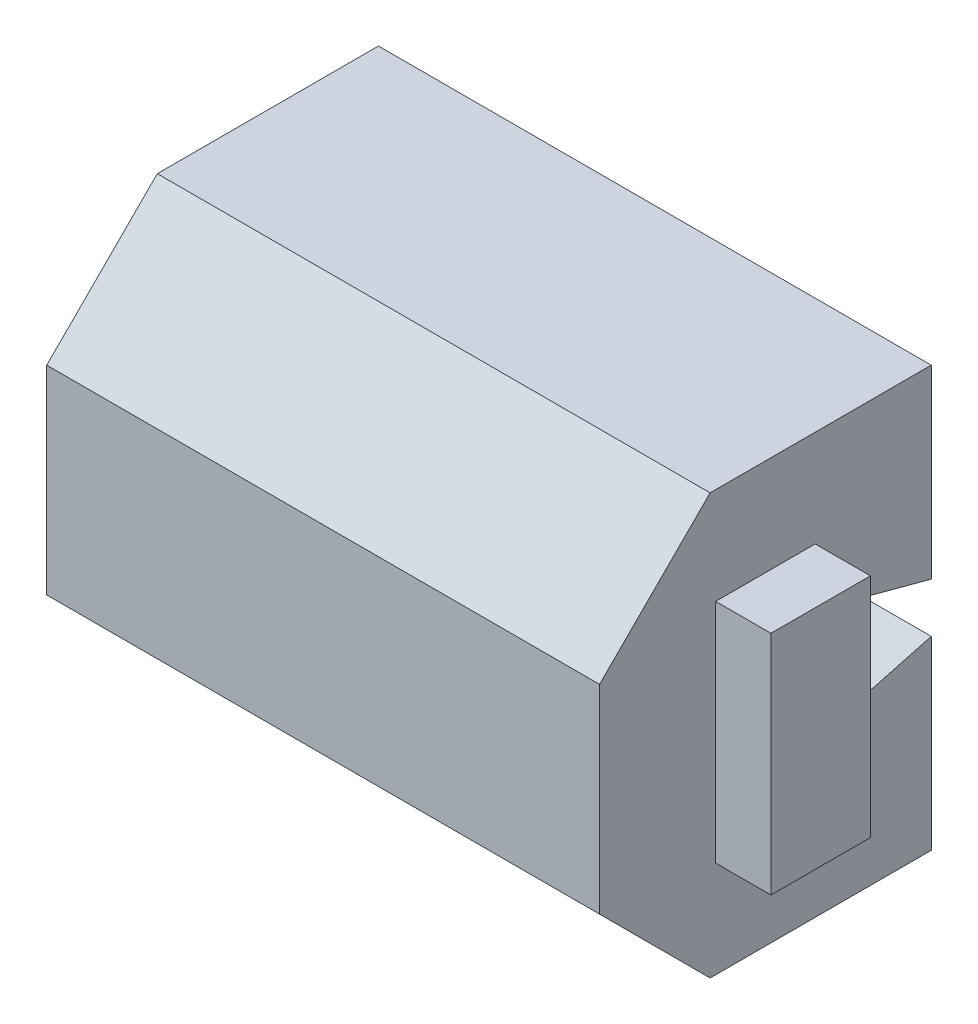
SolidWorks part; units mm, degrees
ref_plane "Piano frontale" through (0, 0, 0) normal (1, 0, 0) x (0, 1, 0)
ref_plane "Piano superiore" through (0, 0, 0) normal (0, 0, 1) x (0, 1, 0)
ref_plane "Piano destro" through (0, 0, 0) normal (0, 1, 0) x (-1, 0, 0)
sketch "Schizzo1" plane through (0, 0, 0) normal (1, 0, 0) x (0, 1, 0)
  line L1 (-10.25, -4.5) -> (10.25, -4.5)
  line L2 (-10.25, -4.5) -> (-10.25, 4.5)
  line L3 (-10.25, 4.5) -> (10.25, 4.5)
  line L4 (10.25, -4.5) -> (10.25, 4.5)
  line L5 (-10.25, -4.5) -> (10.25, 4.5) construction
  line L6 (-10.25, 4.5) -> (10.25, -4.5) construction
  point P0 (0, 0)
  dimension "D1" = 20.5
  dimension "D2" = 9
extrude "Estrusione-Estrusione1" add sketch "Schizzo1" along normal blind 5
sketch "Schizzo2" plane through (0, 0, 0) normal (-1, 0, 0) x (0, -1, 0)
  line L1 (-19, -15) -> (19, -15)
  line L2 (-19, -15) -> (-19, 15)
  line L3 (-19, 15) -> (19, 15)
  line L4 (19, -15) -> (19, 15)
  line L5 (-19, -15) -> (19, 15) construction
  line L6 (-19, 15) -> (19, -15) construction
  point P0 (0, 0)
  dimension "D1" = 30
  dimension "D2" = 38
extrude "Estrusione-Estrusione2" add sketch "Schizzo2" along normal blind 50
sketch "Schizzo3" plane through (-50, 0, 0) normal (-1, 0, 0) x (0, -1, 0)
  line L5 (2.2404, -15) -> (4.25, -7.5)
  line L6 (4.25, -7.5) -> (-4.25, -7.5)
  line L7 (0, -7.5) -> (0, -15) construction
  line L8 (-2.2404, -15) -> (2.2404, -15)
  line L9 (-2.2404, -15) -> (-4.25, -7.5)
  line L10 (-19, -15) -> (19, -15) construction
  dimension "D1" = 8.5
  dimension "D2" = 7.5
  dimension "D3" = 75
extrude "Taglio-Estrusione1" cut sketch "Schizzo3" against normal through all
hole_wizard "M8 Clearance Hole1" positions "Schizzo4" profile "Schizzo6" hole size "M8" standard "ANSI Metric"
sketch "Schizzo4" plane through (-50, 0, 0) normal (-1, 0, 0) x (0, 0, 1)
  line L0 (-15, 19) -> (15, -19) construction
  point P0 (0, 0)
sketch "Schizzo6" plane through (-50, 0, 0) normal (0, 1, 0) x (0, 0, 1)
  line L0 (0, 0) -> (0, 43.0043)
  line L1 (0, 43.0043) -> (5, 40)
  line L2 (5, 40) -> (5, 0)
  line L5 (5, 0) -> (0, 0)
  line L10 (0, 43.0043) -> (-5, 40) construction
  line L11 (0, -6.35) -> (0, 107.95) construction
  dimension "Hole Dia." = 10
  dimension "Hole Depth" = 40
  dimension "Drill Angle" = 118
chamfer "Smusso1" distance 10 angle 45 2 edges at (-25, 19, 15) (-25, -19, 15)
